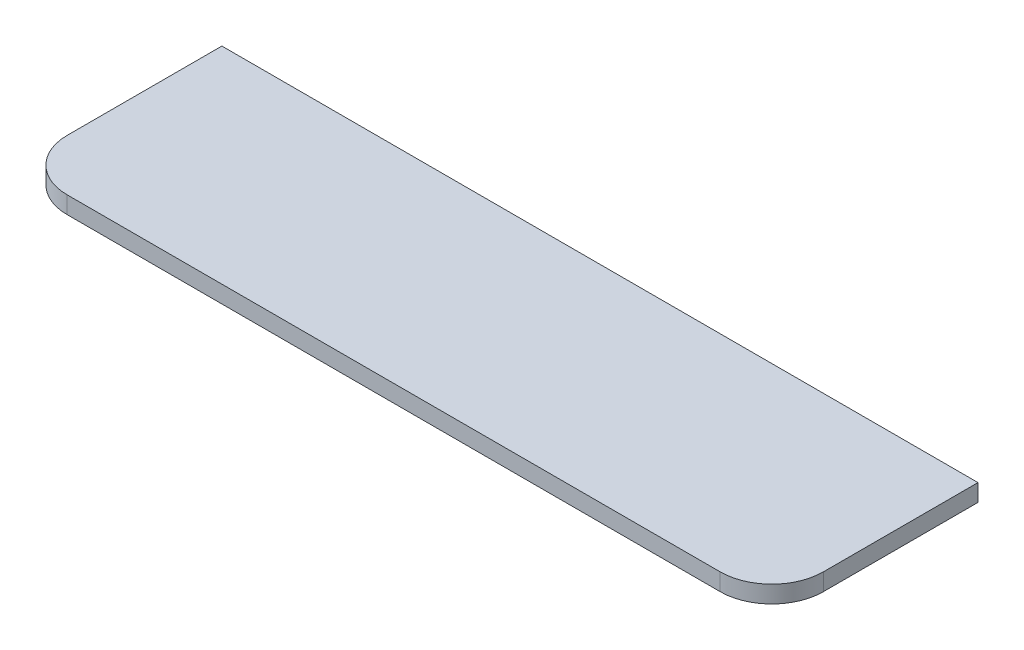
SolidWorks part; units mm, degrees
material "5052-H38, Rod (SS)"
ref_plane "Front Plane" through (0, 0, 0) normal (0, 0, 1) x (1, 0, 0)
ref_plane "Top Plane" through (0, 0, 0) normal (0, 1, 0) x (1, 0, 0)
ref_plane "Right Plane" through (0, 0, 0) normal (1, 0, 0) x (0, 0, -1)
sketch "Sketch1" plane through (0, 0, 0) normal (0, 1, 0) x (1, 0, 0)
  line L1 (-190, -60) -> (190, -60)
  line L2 (-220, -30) -> (-220, 60)
  line L3 (-220, 60) -> (220, 60)
  line L4 (220, -30) -> (220, 60)
  line L5 (-220, -60) -> (220, 60) construction
  line L6 (-220, 60) -> (220, -60) construction
  arc A0 (-190, -60) -> (-220, -30) centre (-190, -30) cw
  arc A1 (190, -60) -> (220, -30) centre (190, -30) ccw
  point P0 (0, 0)
  dimension "D3" = 30
  dimension "D4" = 30
  dimension "D1" = 440
  dimension "D2" = 120
extrude "Boss-Extrude1" add sketch "Sketch1" along normal blind 10
